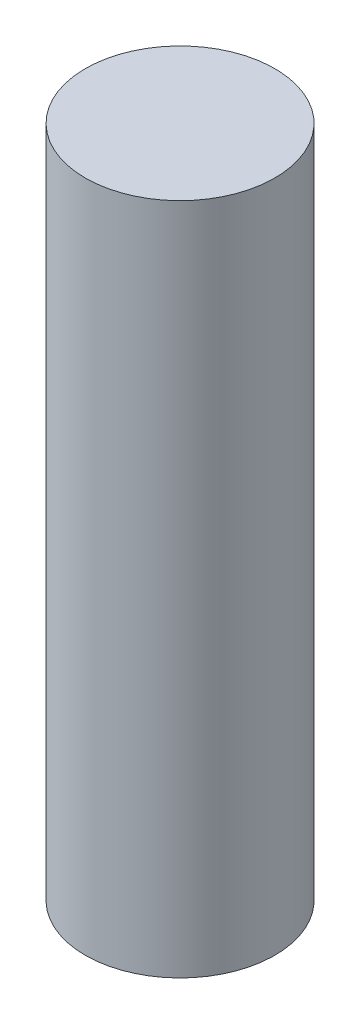
SolidWorks part; units mm, degrees
ref_plane "Front Plane" through (0, 0, 0) normal (0, 0, 1) x (1, 0, 0)
ref_plane "Top Plane" through (0, 0, 0) normal (0, 1, 0) x (1, 0, 0)
ref_plane "Right Plane" through (0, 0, 0) normal (1, 0, 0) x (0, 0, -1)
sketch "Sketch1" plane through (0, 0, 0) normal (0, 1, 0) x (1, 0, 0)
  circle A0 centre (0, 0) radius 9.15
  dimension "D1" = 18.3
extrude "Boss-Extrude1" add sketch "Sketch1" along normal mid plane 65
